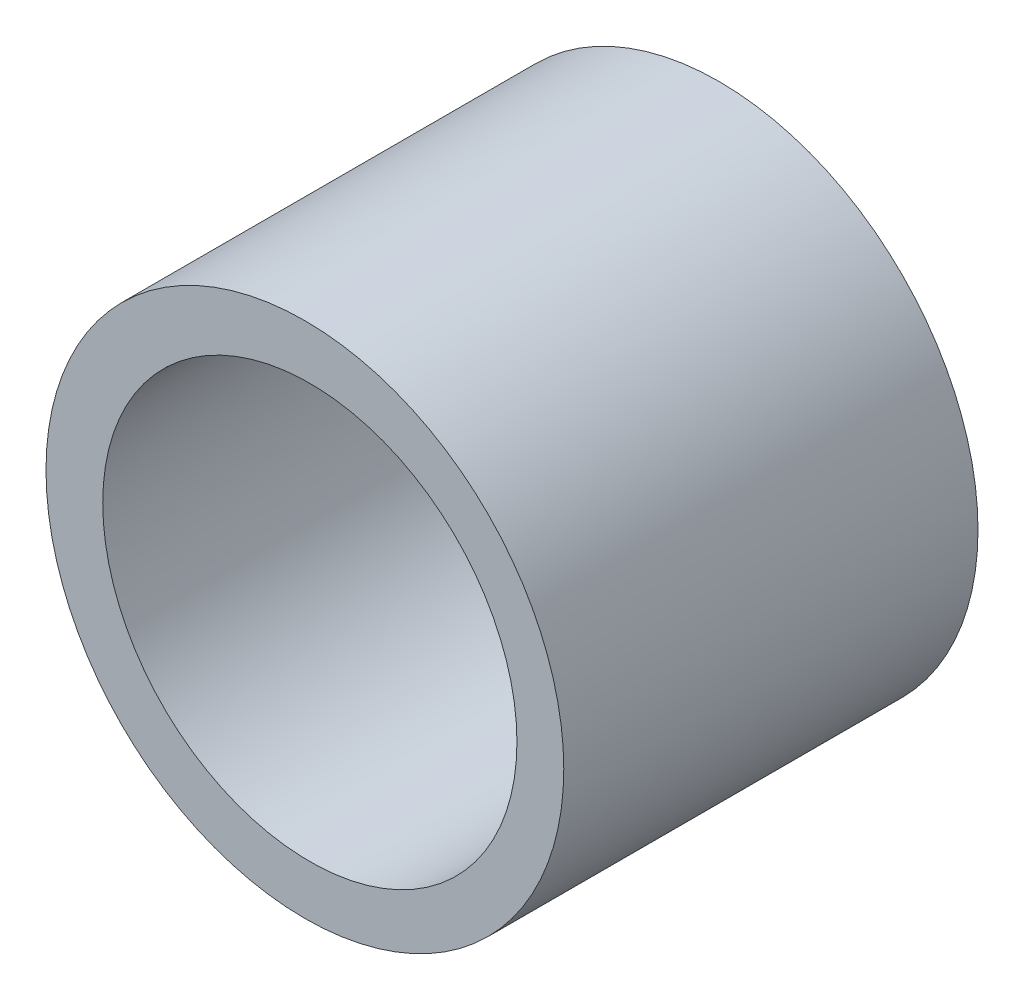
SolidWorks part; units mm, degrees
ref_plane "Ön Düzlem" through (0, 0, 0) normal (0, 0, 1) x (1, 0, 0)
ref_plane "Üst Düzlem" through (0, 0, 0) normal (0, 1, 0) x (1, 0, 0)
ref_plane "Sağ Düzlem" through (0, 0, 0) normal (1, 0, 0) x (0, 0, -1)
sketch "Çizim1" plane through (0, 0, 0) normal (0, 0, 1) x (1, 0, 0)
  circle A0 centre (0, 0) radius 25
  circle A1 centre (0.4784, 0) radius 20
  dimension "D1" = 50
  dimension "D2" = 40
extrude "Yükseklik-Ekstrüzyon1" add sketch "Çizim1" along normal mid plane 40
